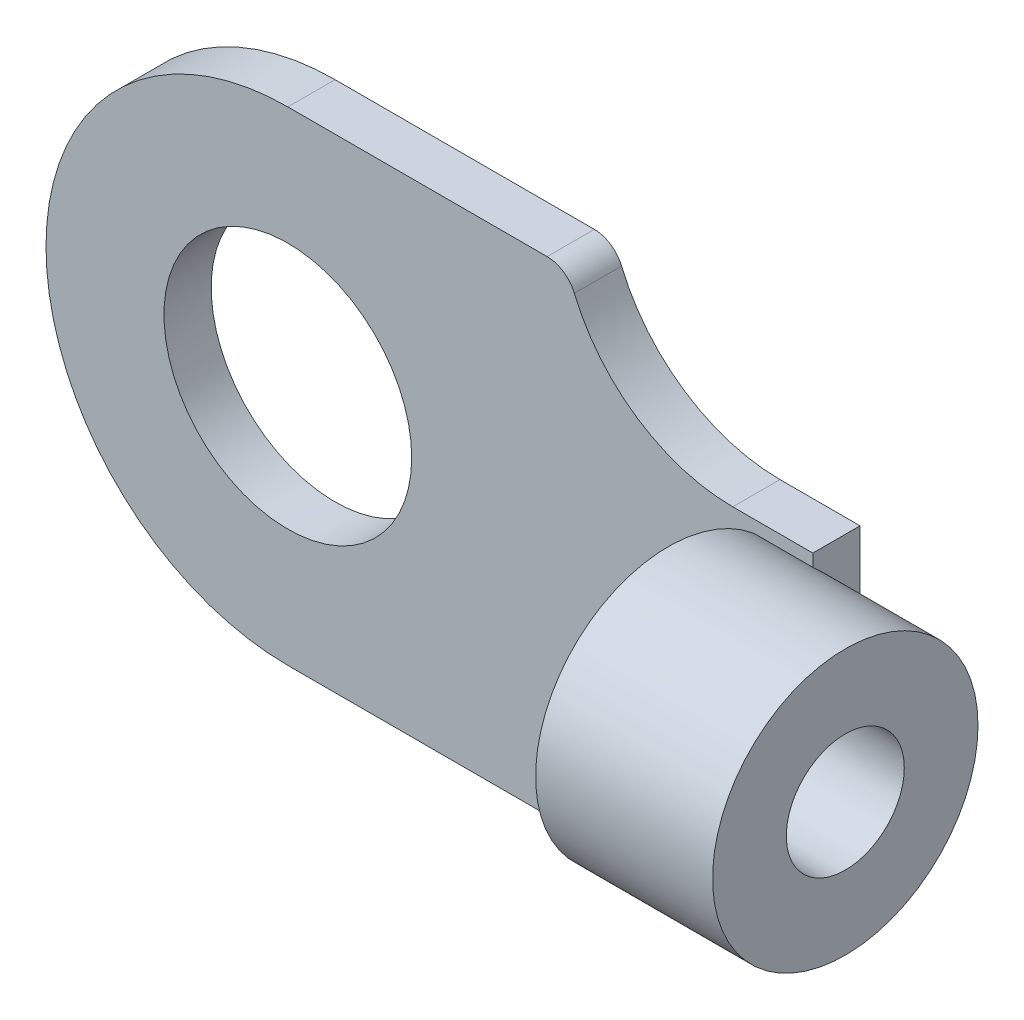
SolidWorks part; units mm, degrees
ref_plane "Спереди" through (0, 0, 0) normal (0, 0, 1) x (1, 0, 0)
ref_plane "Сверху" through (0, 0, 0) normal (0, 1, 0) x (1, 0, 0)
ref_plane "Справа" through (0, 0, 0) normal (1, 0, 0) x (0, 0, -1)
sketch "Эскиз1" plane through (0, 0, 0) normal (0, 0, 1) x (1, 0, 0)
  line L0 (-0.65, -0.0696) -> (21.2934, -0.0696) construction
  line L1 (-0.65, 4.0304) -> (4.0987, 4.0304)
  line L2 (10.25, 1.9304) -> (6.893, 1.9304)
  line L3 (10.25, -2.0696) -> (6.893, -2.0696)
  line L4 (-0.65, -4.1696) -> (4.0987, -4.1696)
  line L5 (10.25, 0.1804) -> (10.25, 1.9304)
  line L9 (10.25, -2.0696) -> (10.25, 0.1804)
  arc A0 (-0.65, 4.0304) -> (-0.65, -4.1696) centre (-0.65, -0.0696) ccw
  circle A1 centre (-0.65, -0.0696) radius 2.1
  arc A2 (4.0987, 4.0304) -> (6.893, 1.9304) centre (6.893, 4.8394) ccw
  arc A3 (4.0987, -4.1696) -> (6.893, -2.0696) centre (6.893, -4.9786) cw
  point P1 (6.893, 1.9304)
  point P5 (10, -2.75)
  dimension "D1" = 15
  dimension "D2" = 2
  dimension "D3" = 8.2
  dimension "D4" = 4.2
extrude "Вытянуть4" add sketch "Эскиз1" along normal blind 0.8
sketch "Эскиз2" plane through (10.25, 0, 0) normal (1, 0, 0) x (0, 0, -1)
  line L0 (0, 0) -> (-5.228, 0) construction
  line L1 (0, -2.0696) -> (0, 1.9304) construction
  circle A0 centre (-2.25, 0) radius 2.25
  circle A1 centre (-2.25, 0) radius 1
  dimension "D1" = 4.5
  dimension "D2" = 2
extrude "Вытянуть5" add sketch "Эскиз2" against normal blind 3
fillet "Скругление1" radius 0.5 2 edges at (4.0987, -4.1696, 0.4) (4.0987, 4.0304, 0.4)
sketch "Эскиз3" plane through (10.25, 0, 0) normal (1, 0, 0) x (0, 0, -1)
  line L1 (-5.5362, -2.9513) -> (1.356, -2.9513)
  line L2 (-5.5362, -2.9513) -> (-5.5362, 2.4409)
  line L3 (-5.5362, 2.4409) -> (1.356, 2.4409)
  line L4 (1.356, -2.9513) -> (1.356, 2.4409)
  circle A0 centre (-2.25, 0) radius 2.25
  arc A1 (-0.8, 1.7205) -> (-0.8, -1.7205) centre (-2.25, 0) ccw construction
extrude "Вырез-Вытянуть1" cut sketch "Эскиз3" against normal blind 2
